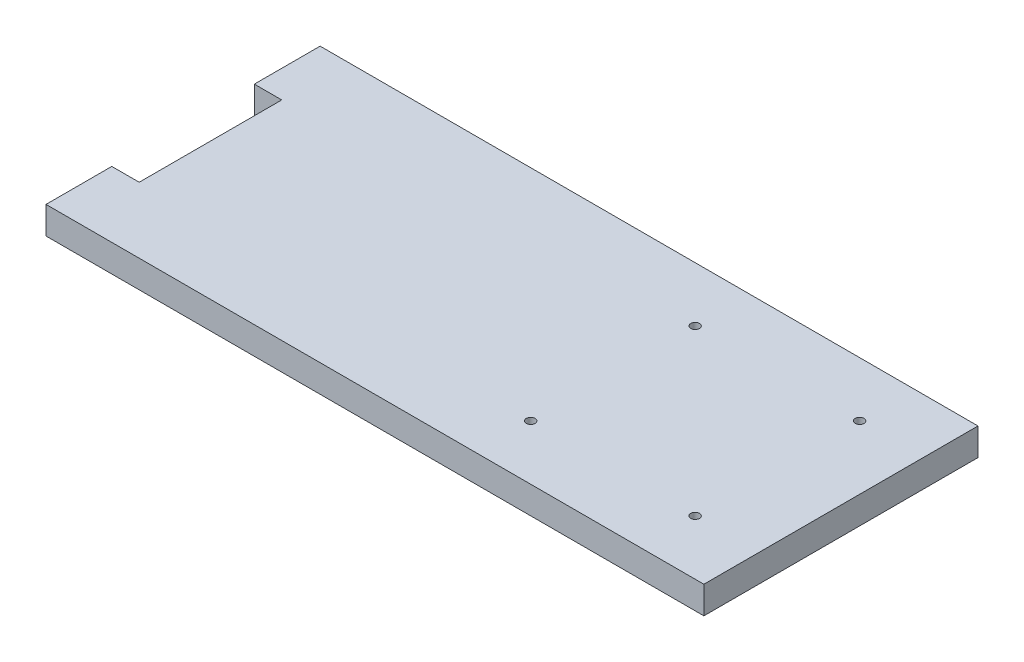
SolidWorks part; units mm, degrees
ref_plane "Front Plane" through (0, 0, 0) normal (0, 0, 1) x (1, 0, 0)
ref_plane "Top Plane" through (0, 0, 0) normal (0, 1, 0) x (1, 0, 0)
ref_plane "Right Plane" through (0, 0, 0) normal (1, 0, 0) x (0, 0, -1)
sketch "Sketch1" plane through (0, 0, 0) normal (0, 1, 0) x (1, 0, 0)
  line L1 (-38.1, 15.875) -> (38.1, 15.875)
  line L2 (-38.1, 15.875) -> (-38.1, -15.875)
  line L3 (-38.1, -15.875) -> (38.1, -15.875)
  line L4 (38.1, 15.875) -> (38.1, -15.875)
  line L5 (-38.1, 15.875) -> (38.1, -15.875) construction
  line L6 (-38.1, -15.875) -> (38.1, 15.875) construction
  point P0 (0, 0)
  dimension "D1" = 31.75
  dimension "D2" = 76.2
extrude "Boss-Extrude1" add sketch "Sketch1" along normal blind 3.175
sketch "Sketch2" plane through (0, 3.175, 0) normal (0, 1, 0) x (1, 0, 0)
  line L0 (-38.1, 15.875) -> (-38.1, -15.875) construction
  line L1 (-38.1, 8.255) -> (-34.925, 8.255)
  line L2 (-38.1, 8.255) -> (-38.1, -8.255)
  line L3 (-38.1, -8.255) -> (-34.925, -8.255)
  line L4 (-34.925, 8.255) -> (-34.925, -8.255)
  line L5 (38.1, 15.875) -> (-38.1, 15.875) construction
  line L6 (-38.1, -15.875) -> (38.1, -15.875) construction
  line L7 (0, 0) -> (38.1, 0) construction
  line L8 (38.1, -15.875) -> (38.1, 15.875) construction
  circle A0 centre (30.737, 9.525) radius 0.508
  circle A1 centre (30.737, -9.525) radius 0.508
  circle A2 centre (11.687, 9.525) radius 0.508
  circle A3 centre (11.687, -9.525) radius 0.508
  dimension "D4" = 6.35
  dimension "D1" = 7.62
  dimension "D2" = 7.62
  dimension "D3" = 3.175
  dimension "D5" = 19.05
  dimension "D6" = 19.05
  dimension "D7" = 6.35
  dimension "D8" = 19.05
  dimension "D9" = 6.35
extrude "Cut-Extrude1" cut sketch "Sketch2" against normal blind 3.175
sketch "Sketch3" plane through (0, 3.175, 0) normal (0, 1, 0) x (1, 0, 0)
  circle A0 centre (21.212, 0) radius 3.6689 construction
